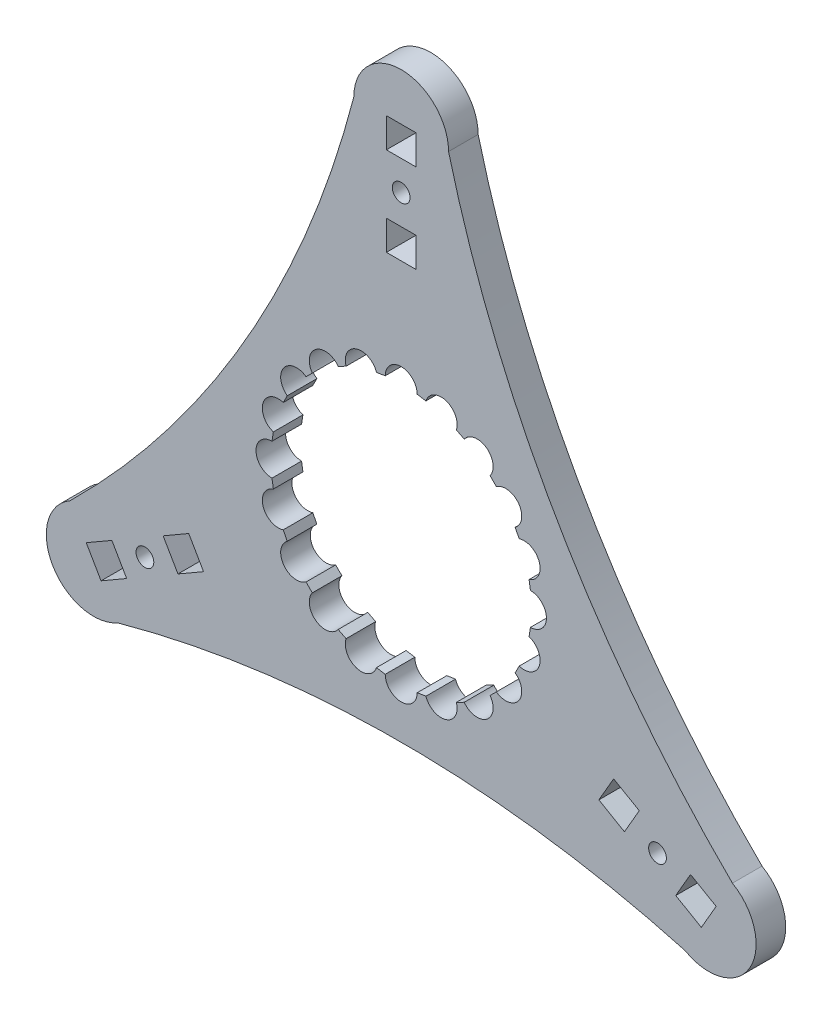
SolidWorks part; units mm, degrees
ref_plane "Front Plane" through (0, 0, 0) normal (0, 0, 1) x (1, 0, 0)
ref_plane "Top Plane" through (0, 0, 0) normal (0, 1, 0) x (1, 0, 0)
ref_plane "Right Plane" through (0, 0, 0) normal (1, 0, 0) x (0, 0, -1)
sketch "Esquisse1" plane through (0, 0, 0) normal (0, 0, 1) x (1, 0, 0)
  line L0 (0, 0) -> (0, 68) construction
  line L1 (0, 0) -> (58.8897, -34) construction
  line L2 (0, 0) -> (-58.8897, -34) construction
  line L3 (0, -9.2376) -> (47.9615, -36.9282) construction
  line L4 (-8, 4.6188) -> (-46.7434, -17.7497) construction
  line L5 (8, 4.6188) -> (8, 60) construction
  line L6 (8, 4.6188) -> (55.9615, -23.0718) construction
  line L7 (0, -9.2376) -> (-47.9615, -36.9282) construction
  line L8 (-8, 4.6188) -> (-8, 60) construction
  line L9 (-55.9615, -23.0718) -> (-46.7434, -17.7497) construction
  line L10 (-38.7434, -31.6061) -> (-47.9615, -36.9282) construction
  line L11 (47.9615, -36.9282) -> (38.7434, -31.6061) construction
  line L12 (-8, 60) -> (-8, 49.3559) construction
  line L13 (8, 60) -> (8, 49.3559) construction
  line L14 (55.9615, -23.0718) -> (46.7434, -17.7497) construction
  line L15 (-2.7, 21.8337) -> (2.7, 21.8337) construction
  line L17 (2.7, 21.8337) -> (4.1791, 21.5994)
  line L19 (9.3148, 19.9307) -> (10.6492, 19.2508)
  line L20 (15.0179, 16.0768) -> (16.0768, 15.0179)
  line L21 (19.2508, 10.6492) -> (19.9307, 9.3148)
  line L22 (21.5994, 4.1791) -> (21.8337, 2.7)
  line L23 (21.8337, -2.7) -> (21.5994, -4.1791)
  line L24 (19.9307, -9.3148) -> (19.2508, -10.6492)
  line L25 (16.0768, -15.0179) -> (15.0179, -16.0768)
  line L26 (10.6492, -19.2508) -> (9.3148, -19.9307)
  line L27 (4.1791, -21.5994) -> (2.7, -21.8337)
  line L28 (-2.7, -21.8337) -> (-4.1791, -21.5994)
  line L29 (-9.3148, -19.9307) -> (-10.6492, -19.2508)
  line L30 (-15.0179, -16.0768) -> (-16.0768, -15.0179)
  line L31 (-19.2508, -10.6492) -> (-19.9307, -9.3148)
  line L32 (-21.5994, -4.1791) -> (-21.8337, -2.7)
  line L33 (-21.8337, 2.7) -> (-21.5994, 4.1791)
  line L34 (-19.9307, 9.3148) -> (-19.2508, 10.6492)
  line L35 (-16.0768, 15.0179) -> (-15.0179, 16.0768)
  line L36 (-10.6492, 19.2508) -> (-9.3148, 19.9307)
  line L37 (-4.1791, 21.5994) -> (-2.7, 21.8337)
  arc A0 (-55.9615, -23.0718) -> (-47.9615, -36.9282) centre (-51.9615, -30) ccw
  arc A1 (55.9615, -23.0718) -> (47.9615, -36.9282) centre (51.9615, -30) cw
  arc A2 (8, 60) -> (-8, 60) centre (0, 60) ccw
  circle A3 centre (0, 0) radius 25.5 construction
  circle A4 centre (0, 0) radius 50 construction
  arc A5 (8, 49.3559) -> (46.7434, -17.7497) centre (0, 0) cw construction
  arc A6 (-8, 49.3559) -> (-46.7434, -17.7497) centre (0, 0) ccw construction
  arc A7 (-38.7434, -31.6061) -> (38.7434, -31.6061) centre (0, 0) ccw construction
  circle A8 centre (0, 0) radius 22 construction
  arc A13 (2.7, 21.8337) -> (-2.7, 21.8337) centre (0, 21.8337) ccw
  arc A14 (9.3148, 19.9307) -> (4.1791, 21.5994) centre (6.747, 20.7651) ccw
  arc A15 (15.0179, 16.0768) -> (10.6492, 19.2508) centre (12.8335, 17.6638) ccw
  arc A16 (19.2508, 10.6492) -> (16.0768, 15.0179) centre (17.6638, 12.8335) ccw
  arc A17 (21.5994, 4.1791) -> (19.9307, 9.3148) centre (20.7651, 6.747) ccw
  arc A18 (21.8337, -2.7) -> (21.8337, 2.7) centre (21.8337, 0) ccw
  arc A19 (19.9307, -9.3148) -> (21.5994, -4.1791) centre (20.7651, -6.747) ccw
  arc A20 (16.0768, -15.0179) -> (19.2508, -10.6492) centre (17.6638, -12.8335) ccw
  arc A21 (10.6492, -19.2508) -> (15.0179, -16.0768) centre (12.8335, -17.6638) ccw
  arc A22 (4.1791, -21.5994) -> (9.3148, -19.9307) centre (6.747, -20.7651) ccw
  arc A23 (-2.7, -21.8337) -> (2.7, -21.8337) centre (0, -21.8337) ccw
  arc A24 (-9.3148, -19.9307) -> (-4.1791, -21.5994) centre (-6.747, -20.7651) ccw
  arc A25 (-15.0179, -16.0768) -> (-10.6492, -19.2508) centre (-12.8335, -17.6638) ccw
  arc A26 (-19.2508, -10.6492) -> (-16.0768, -15.0179) centre (-17.6638, -12.8335) ccw
  arc A27 (-21.5994, -4.1791) -> (-19.9307, -9.3148) centre (-20.7651, -6.747) ccw
  arc A28 (-21.8337, 2.7) -> (-21.8337, -2.7) centre (-21.8337, 0) ccw
  arc A29 (-19.9307, 9.3148) -> (-21.5994, 4.1791) centre (-20.7651, 6.747) ccw
  arc A30 (-16.0768, 15.0179) -> (-19.2508, 10.6492) centre (-17.6638, 12.8335) ccw
  arc A31 (-10.6492, 19.2508) -> (-15.0179, 16.0768) centre (-12.8335, 17.6638) ccw
  arc A32 (-4.1791, 21.5994) -> (-9.3148, 19.9307) centre (-6.747, 20.7651) ccw
  arc A33 (8, 60) -> (55.9615, -23.0718) centre (182.2298, 105.2104) ccw
  arc A34 (47.9615, -36.9282) -> (-47.9615, -36.9282) centre (0, -210.4208) ccw
  arc A35 (-55.9615, -23.0718) -> (-8, 60) centre (-182.2298, 105.2104) ccw
  point P38 (58.8897, -34)
  point P40 (-58.8897, -34)
  point P92 (0, 0)
  point P99 (0, 0)
  point P101 (0, 0)
  point P109 (0, 0)
  point P110 (0, 0)
  point P134 (0, 0)
  line B0 (38.9711, -22.5) -> (47.6314, -27.5) construction
  line B1 (40.2211, -20.3349) -> (35.891, -17.8349)
  line B2 (40.2211, -20.3349) -> (37.7211, -24.6651)
  line B3 (37.7211, -24.6651) -> (33.391, -22.1651)
  line B4 (35.891, -17.8349) -> (33.391, -22.1651)
  line B5 (48.8814, -25.3349) -> (53.2115, -27.8349)
  line B6 (48.8814, -25.3349) -> (46.3814, -29.6651)
  line B7 (46.3814, -29.6651) -> (50.7115, -32.1651)
  line B8 (53.2115, -27.8349) -> (50.7115, -32.1651)
  line B9 (43.3013, -25) -> (46.7875, -18.9617) construction
  circle B10 centre (43.3013, -25) radius 1.5
  line B11 (0, 55) -> (0, 45) construction
  line B12 (2.5, 55) -> (2.5, 60)
  line B13 (2.5, 55) -> (-2.5, 55)
  line B14 (-2.5, 55) -> (-2.5, 60)
  line B15 (2.5, 60) -> (-2.5, 60)
  line B16 (2.5, 45) -> (2.5, 40)
  line B17 (2.5, 45) -> (-2.5, 45)
  line B18 (-2.5, 45) -> (-2.5, 40)
  line B19 (2.5, 40) -> (-2.5, 40)
  line B20 (0, 50) -> (6.9724, 50) construction
  circle B21 centre (0, 50) radius 1.5
  line B22 (-47.6314, -27.5) -> (-38.9711, -22.5) construction
  line B23 (-48.8814, -25.3349) -> (-53.2115, -27.8349)
  line B24 (-48.8814, -25.3349) -> (-46.3814, -29.6651)
  line B25 (-46.3814, -29.6651) -> (-50.7115, -32.1651)
  line B26 (-53.2115, -27.8349) -> (-50.7115, -32.1651)
  line B27 (-40.2211, -20.3349) -> (-35.891, -17.8349)
  line B28 (-40.2211, -20.3349) -> (-37.7211, -24.6651)
  line B29 (-37.7211, -24.6651) -> (-33.391, -22.1651)
  line B30 (-35.891, -17.8349) -> (-33.391, -22.1651)
  line B31 (-43.3013, -25) -> (-46.7875, -18.9617) construction
  circle B32 centre (-43.3013, -25) radius 1.5
  dimension "D1" = 51
  dimension "D3" = 8
  dimension "D5" = 2.7
  dimension "D6" = 44
  dimension "D9" = 3
  dimension "D10" = 180
  dimension "D2" = 50
  dimension "D4" = 120
  dimension "D7" = 20
  dimension "D8" = 20
sketch_block_instance "Trou M3 plots 5mm-2-18"
sketch_block "Trou M3 plots 5mm-2" parameters "D2"=3, "D1"=5, "D3"=5, "D4"=10
sketch_block_instance "Trou M3 plots 5mm-2-19"
sketch_block_instance "Trou M3 plots 5mm-2-20"
extrude "Boss.-Extru.1" add sketch "Esquisse1" along normal blind 5
